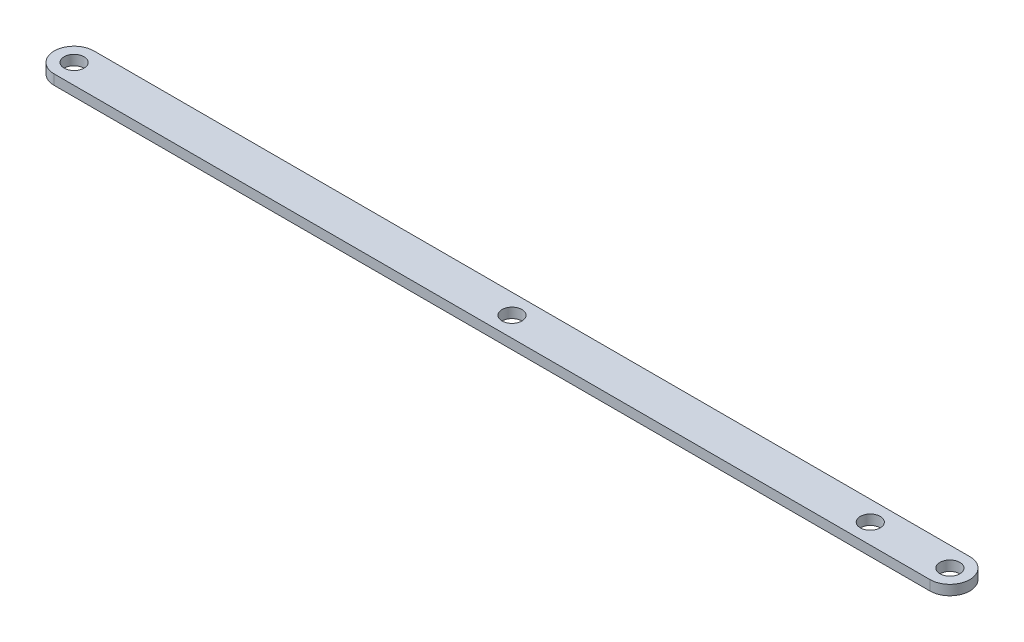
SolidWorks part; units mm, degrees
ref_plane "Front Plane" through (0, 0, 0) normal (0, 0, 1) x (1, 0, 0)
ref_plane "Top Plane" through (0, 0, 0) normal (0, 1, 0) x (1, 0, 0)
ref_plane "Right Plane" through (0, 0, 0) normal (1, 0, 0) x (0, 0, -1)
sketch "Sketch1" plane through (0, 0, 0) normal (0, 1, 0) x (1, 0, 0)
  line L0 (-72.3468, 0) -> (367.6532, 0) construction
  line L1 (-72.3468, 10) -> (367.6532, 10)
  line L2 (-72.3468, -10) -> (367.6532, -10)
  arc A0 (-72.3468, 10) -> (-72.3468, -10) centre (-72.3468, 0) ccw
  arc A1 (367.6532, -10) -> (367.6532, 10) centre (367.6532, 0) ccw
  circle A2 centre (-72.3468, 0) radius 5
  circle A3 centre (367.6532, 0) radius 5
  point P3 (147.6532, 0)
  dimension "D1" = 440
  dimension "D2" = 10
  dimension "D3" = 10
  dimension "D4" = 10
extrude "Boss-Extrude1" add sketch "Sketch1" along normal blind 5
sketch "Sketch3" plane through (0, 5, 0) normal (0, 1, 0) x (1, 0, 0)
  line L0 (367.6532, 10) -> (-72.3468, 10) construction
  circle A0 centre (327.6532, 0) radius 5
  circle A1 centre (147.6532, 0) radius 5
  arc A2 (367.6532, -10) -> (367.6532, 10) centre (367.6532, 0) ccw construction
  circle A3 centre (367.6532, 0) radius 5 construction
  point P7 (377.6532, 0)
  dimension "D1" = 10
  dimension "D2" = 10
  dimension "D7" = 40
  dimension "D3" = 50
  dimension "D4" = 180
  dimension "D5" = 10
  dimension "D6" = 10
extrude "Cut-Extrude1" cut sketch "Sketch3" against normal blind 10
